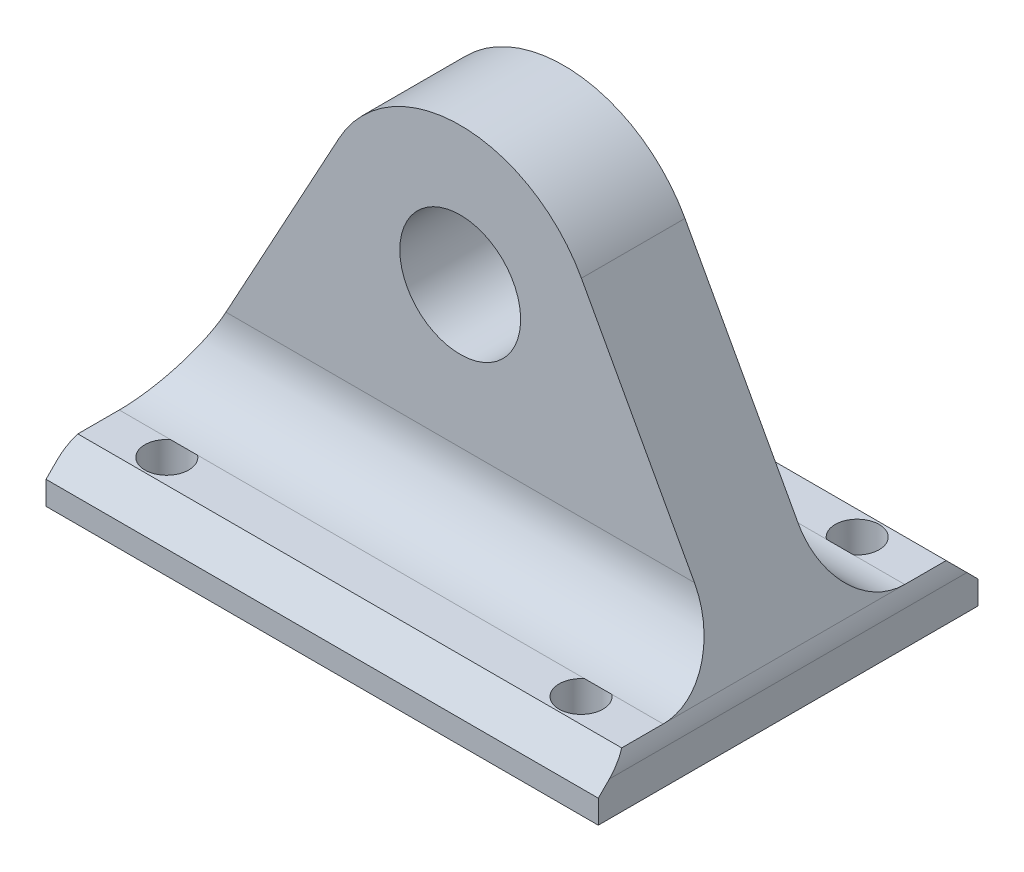
SolidWorks part; units mm, degrees
material "6061-T6 (SS)"
ref_plane "Front Plane" through (0, 0, 0) normal (0, 0, 1) x (1, 0, 0)
ref_plane "Top Plane" through (0, 0, 0) normal (0, 1, 0) x (1, 0, 0)
ref_plane "Right Plane" through (0, 0, 0) normal (1, 0, 0) x (0, 0, -1)
sketch "Sketch1" plane through (0, 0, 0) normal (0, 0, 1) x (1, 0, 0)
  line L0 (0, -3.175) -> (44.45, -3.175)
  line L1 (-2.7869, 1.5212) -> (11.0775, 26.9212)
  line L2 (33.3725, 26.9212) -> (47.2369, 1.5212)
  line L3 (-25.4, 0) -> (44.45, 0) construction
  line L4 (-3.175, 0) -> (-3.175, -3.175)
  line L5 (-3.175, -3.175) -> (0, -3.175)
  line L6 (47.625, 0) -> (47.625, -3.175)
  line L7 (47.625, -3.175) -> (44.45, -3.175)
  arc A0 (33.3725, 26.9212) -> (11.0775, 26.9212) centre (22.225, 20.8364) ccw
  circle A1 centre (22.225, 20.8364) radius 5.5562
  arc A2 (-2.7869, 1.5212) -> (-3.175, 0) centre (0, 0) ccw
  arc A3 (47.625, 0) -> (47.2369, 1.5212) centre (44.45, 0) ccw
  dimension "D1" = 6.35
  dimension "D2" = 11.1125
  dimension "D3" = 25.4
  dimension "D4" = 44.45
  dimension "D5" = 25.4
extrude "Boss-Extrude1" add sketch "Sketch1" along normal blind 9.525
ref_plane "Plane1" through (0, 15.875, 0) normal (0, -1, 0) x (-1, 0, 0)
sketch "Sketch4" plane through (0, 0, 9.525) normal (0, 0, 1) x (1, 0, 0)
  line L0 (47.2369, 1.5212) -> (33.3725, 26.9212) construction
  line L1 (47.625, -3.175) -> (47.625, 0) construction
  line L2 (-3.175, -3.175) -> (47.625, -3.175) construction
  line L3 (11.0775, 26.9212) -> (-2.7869, 1.5212) construction
  line L4 (-3.175, 0) -> (-3.175, -3.175) construction
  line L5 (47.2369, 1.5212) -> (33.3725, 26.9212) construction
  line L6 (47.625, -3.175) -> (47.625, 0)
  line L7 (-3.175, -3.175) -> (47.625, -3.175)
  line L8 (11.0775, 26.9212) -> (-2.7869, 1.5212) construction
  line L9 (-3.175, 0) -> (-3.175, -3.175)
  line L10 (-2.7869, 1.5212) -> (47.2369, 1.5212)
  arc A0 (47.625, 0) -> (47.2369, 1.5212) centre (44.45, 0) ccw construction
  arc A1 (-2.7869, 1.5212) -> (-3.175, 0) centre (0, 0) ccw construction
  arc A2 (47.625, 0) -> (47.2369, 1.5212) centre (44.45, 0) ccw
  arc A3 (-2.7869, 1.5212) -> (-3.175, 0) centre (0, 0) ccw
extrude "Boss-Extrude2" add sketch "Sketch4" along normal blind 12.7
chamfer "Chamfer3" distance 2.54 angle 45 1 edges at (22.225, 1.5212, 22.225)
sketch "Sketch6" plane through (0, 0, 0) normal (0, 0, -1) x (-1, 0, 0)
  line L0 (3.175, 0) -> (3.175, -3.175) construction
  line L1 (3.175, -3.175) -> (-47.625, -3.175) construction
  line L2 (-47.625, -3.175) -> (-47.625, 0) construction
  line L3 (3.175, 0) -> (3.175, -3.175)
  line L4 (3.175, -3.175) -> (-47.625, -3.175)
  line L5 (-47.625, -3.175) -> (-47.625, 0)
  line L6 (-47.2369, 1.5212) -> (2.7869, 1.5212)
  arc A0 (3.175, 0) -> (2.7869, 1.5212) centre (0, 0) ccw construction
  arc A1 (-47.2369, 1.5212) -> (-47.625, 0) centre (-44.45, 0) ccw construction
  arc A2 (3.175, 0) -> (2.7869, 1.5212) centre (0, 0) ccw
  arc A3 (-47.2369, 1.5212) -> (-47.625, 0) centre (-44.45, 0) ccw
extrude "Boss-Extrude3" add sketch "Sketch6" along normal blind 12.7
chamfer "Chamfer4" distance 2.54 angle 45 1 edges at (22.225, 1.5212, -12.7)
fillet "Fillet4" radius 6.35 2 edges at (22.225, 1.5212, 0) (22.225, 1.5212, 9.525)
sketch "Sketch7" plane through (0, 1.5212, 0) normal (0, 1, 0) x (1, 0, 0)
  line L2 (-3.175, -21.2062) -> (-3.175, 11.6812) construction
  line L5 (-3.175, -4.7625) -> (47.2369, -4.7625) construction
  line L6 (47.2369, -15.875) -> (47.2369, 6.35) construction
  point P0 (3.175, 7.9375)
  point P1 (41.275, 7.9375)
  point P2 (41.275, -17.4625)
  point P3 (3.175, -17.4625)
  dimension "D1" = 25.4
  dimension "D2" = 38.1
  dimension "D3" = 6.35
  dimension "D4" = 12.7
hole_wizard "#10-32 Tapped Hole1" positions "3DSketch3" profile "Sketch9" tap size "#10-32" standard "ANSI Inch"
sketch3d "3DSketch3"
  point P0 (3.175, 1.5212, -7.9375)
  point P3 (41.275, 1.5212, -7.9375)
  point P6 (41.275, 1.5212, 17.4625)
  point P9 (3.175, 1.5212, 17.4625)
sketch "Sketch9" plane through (3.175, 1.5212, -7.9375) normal (1, 0, 0) x (0, 0, 1)
  line L0 (0, 0) -> (0, 4.6962)
  line L1 (0, 4.6962) -> (2.0193, 4.6962)
  line L2 (2.0193, 4.6962) -> (2.0193, 0)
  line L5 (2.0193, 0) -> (0, 0)
  line L11 (0, -6.35) -> (0, 107.95) construction
  dimension "Thru Tap Drill Dia." = 4.0386
  dimension "Thru Tap Drill Depth" = 4.6962
cosmetic thread "Hole Thread1" parameters "D2"=4.826
cosmetic thread "Hole Thread2" parameters "D2"=4.826
cosmetic thread "Hole Thread3" parameters "D2"=4.826
cosmetic thread "Hole Thread4" parameters "D2"=4.826
equation "\"D3@Sketch7\"=(2-\"D2@Sketch7\")/2"
